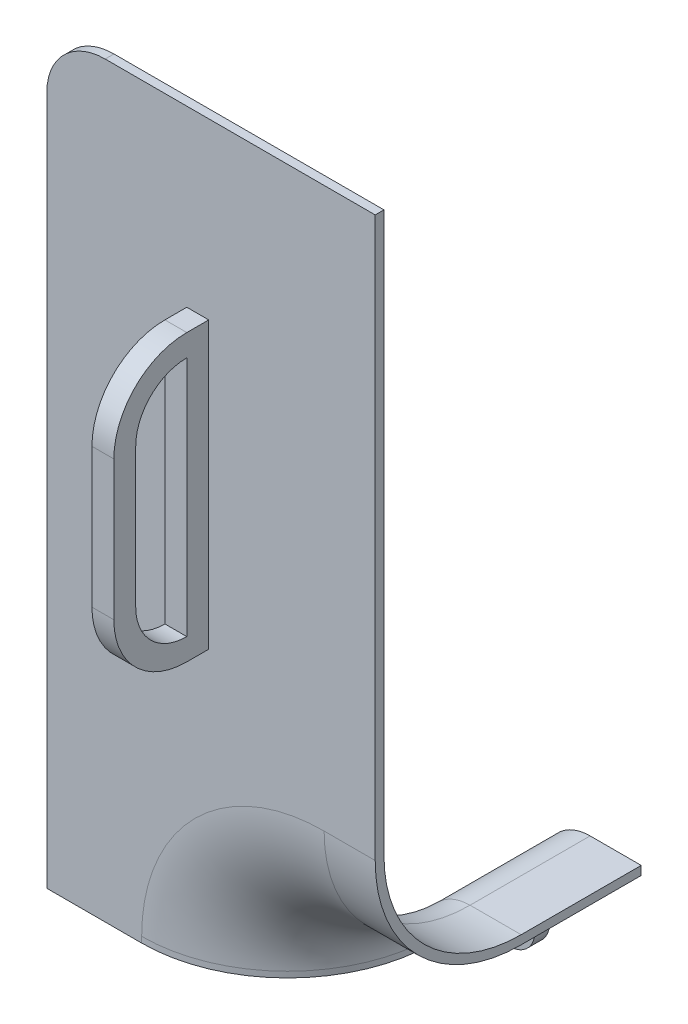
SolidWorks part; units mm, degrees
ref_plane "Front Plane" through (0, 0, 0) normal (0, 0, 1) x (1, 0, 0)
ref_plane "Top Plane" through (0, 0, 0) normal (0, 1, 0) x (1, 0, 0)
ref_plane "Right Plane" through (0, 0, 0) normal (1, 0, 0) x (0, 0, -1)
sketch "Sketch1" plane through (0, 0, 0) normal (0, 0, 1) x (1, 0, 0)
  line L0 (-72.7315, -496.2154) -> (-35.7315, -496.2154)
  line L2 (-35.7315, -496.2154) -> (-35.7315, -592.8312)
  line L3 (-47.7315, -598.6272) -> (-80.7315, -598.6272)
  line L4 (-80.7315, -598.6272) -> (-80.7315, -504.2154)
  line L10 (-35.7315, -592.8312) -> (-47.7315, -592.8312)
  line L11 (-47.7315, -598.6272) -> (-47.7315, -592.8312)
  arc A1 (-72.7315, -496.2154) -> (-80.7315, -504.2154) centre (-72.7315, -504.2154) ccw
  dimension "D2" = 45
extrude "Boss-Extrude1" add sketch "Sketch1" along normal offset from surface (36.45 mm away) 3
fillet "Fillet1" radius 5 1 edges at (-47.7315, -592.8312, 18.225)
fillet "Fillet2" radius 20 3 edges at (-47.7315, -598.2292, 36.45) (-39.2315, -592.8312, 36.45) (-46.267, -594.2956, 36.45)
shell "Shell2" thickness 1.2
sketch "Sketch3" plane through (0, 0, 8) normal (0, 0, 1) x (1, 0, 0)
  line L4 (-47.7315, -597.8312) -> (-47.7315, -600.2705)
  line L5 (-47.7315, -600.2705) -> (-43.7922, -600.2705)
  line L6 (-40.2922, -596.7705) -> (-40.2922, -592.8312)
  line L7 (-40.2922, -592.8312) -> (-42.7315, -592.8312)
  line L8 (-47.7315, -597.8312) -> (-47.7315, -600.2705)
  line L9 (-47.7315, -600.2705) -> (-43.7922, -600.2705)
  line L10 (-40.2922, -596.7705) -> (-40.2922, -592.8312)
  line L11 (-40.2922, -592.8312) -> (-42.7315, -592.8312)
  circle A1 centre (-43.7922, -596.7705) radius 1.5
  arc A2 (-42.7315, -592.8312) -> (-47.7315, -597.8312) centre (-42.7315, -597.8312) ccw
  arc A3 (-43.7922, -600.2705) -> (-40.2922, -596.7705) centre (-43.7922, -596.7705) ccw
  arc A4 (-42.7315, -592.8312) -> (-47.7315, -597.8312) centre (-42.7315, -597.8312) ccw
  arc A5 (-43.7922, -600.2705) -> (-40.2922, -596.7705) centre (-43.7922, -596.7705) ccw
  dimension "D1" = 0
extrude "Boss-Extrude2" add sketch "Sketch3" along normal blind 2
sketch "Sketch4" plane through (0, 0, 36.45) normal (0, 0, 1) x (1, 0, 0)
  line L1 (-61.5453, -520.0813) -> (-58.5453, -520.0813)
  line L2 (-61.5453, -520.0813) -> (-61.5453, -559.1646)
  line L3 (-61.5453, -559.1646) -> (-58.5453, -559.1646)
  line L4 (-58.5453, -520.0813) -> (-58.5453, -559.1646)
  dimension "D1" = 3
extrude "Boss-Extrude3" add sketch "Sketch4" along normal blind 13
fillet "Fillet3" radius 10 2 edges at (-60.0453, -559.1646, 49.45) (-60.0453, -520.0813, 49.45)
sketch "Sketch5" plane through (-58.5453, 0, 0) normal (1, 0, 0) x (0, 0, -1)
  line L4 (-49.45, -530.0813) -> (-49.45, -549.1646)
  line L5 (-39.45, -559.1646) -> (-36.45, -559.1646)
  line L6 (-36.45, -559.1646) -> (-36.45, -520.0813)
  line L7 (-36.45, -520.0813) -> (-39.45, -520.0813)
  line L8 (-49.45, -530.0813) -> (-49.45, -549.1646)
  line L9 (-39.45, -559.1646) -> (-36.45, -559.1646)
  line L10 (-36.45, -559.1646) -> (-36.45, -520.0813)
  line L11 (-36.45, -520.0813) -> (-39.45, -520.0813)
  line L16 (-46.45, -530.0813) -> (-46.45, -549.1646)
  line L17 (-39.45, -556.1646) -> (-39.45, -523.0813)
  line L18 (-46.45, -530.0813) -> (-46.45, -549.1646)
  line L19 (-39.45, -556.1646) -> (-39.45, -523.0813)
  arc A2 (-49.45, -549.1646) -> (-39.45, -559.1646) centre (-39.45, -549.1646) ccw
  arc A3 (-39.45, -520.0813) -> (-49.45, -530.0813) centre (-39.45, -530.0813) ccw
  arc A4 (-49.45, -549.1646) -> (-39.45, -559.1646) centre (-39.45, -549.1646) ccw
  arc A5 (-39.45, -520.0813) -> (-49.45, -530.0813) centre (-39.45, -530.0813) ccw
  arc A8 (-46.45, -549.1646) -> (-39.45, -556.1646) centre (-39.45, -549.1646) ccw
  arc A9 (-39.45, -523.0813) -> (-46.45, -530.0813) centre (-39.45, -530.0813) ccw
  arc A10 (-46.45, -549.1646) -> (-39.45, -556.1646) centre (-39.45, -549.1646) ccw
  arc A11 (-39.45, -523.0813) -> (-46.45, -530.0813) centre (-39.45, -530.0813) ccw
  dimension "D1" = 0
  dimension "D2" = 3
extrude "Cut-Extrude1" cut sketch "Sketch5" against normal blind 13 contours L19 A11 L18 A10
